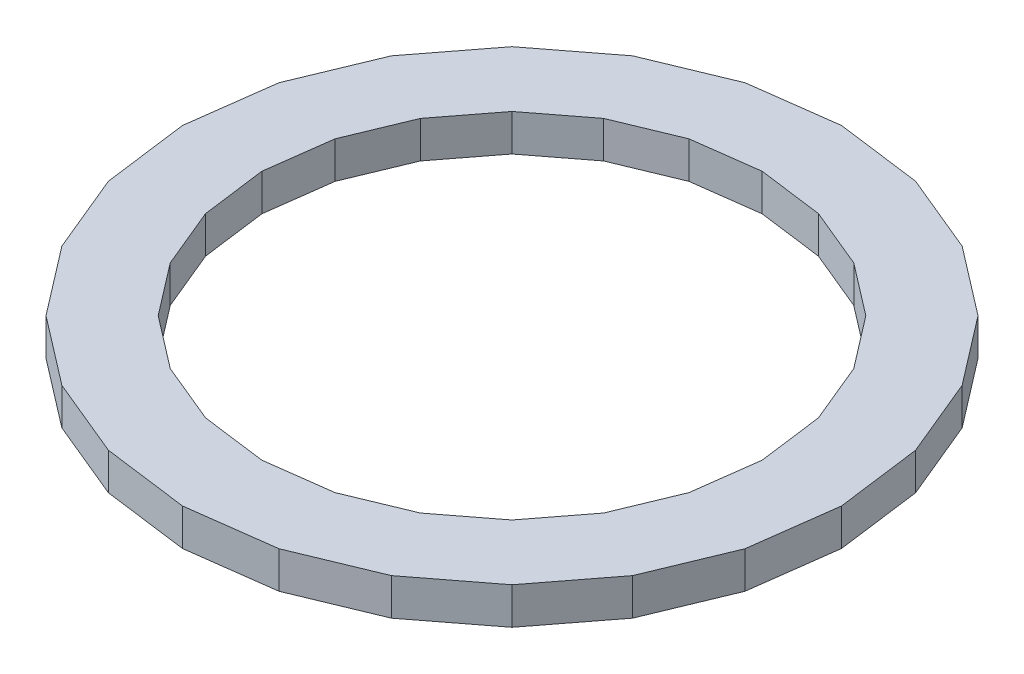
SolidWorks part; units mm, degrees
ref_plane "Front Plane" through (0, 0, 0) normal (0, 0, 1) x (1, 0, 0)
ref_plane "Top Plane" through (0, 0, 0) normal (0, 1, 0) x (1, 0, 0)
ref_plane "Right Plane" through (0, 0, 0) normal (1, 0, 0) x (0, 0, -1)
sketch "Sketch2" plane through (0, 0, 0) normal (0, 1, 0) x (1, 0, 0)
  line L0 (0, 0) -> (-129.2817, 0) construction
  line L1 (-170.2723, 0) -> (-164.4704, -44.0697)
  line L2 (-164.4704, -44.0697) -> (-147.4602, -85.1362)
  line L3 (-147.4602, -85.1362) -> (-120.4007, -120.4007)
  line L4 (-120.4007, -120.4007) -> (-85.1362, -147.4602)
  line L5 (-85.1362, -147.4602) -> (-44.0697, -164.4704)
  line L6 (-44.0697, -164.4704) -> (0, -170.2723)
  line L7 (0, -170.2723) -> (44.0697, -164.4704)
  line L8 (44.0697, -164.4704) -> (85.1362, -147.4602)
  line L9 (85.1362, -147.4602) -> (120.4007, -120.4007)
  line L10 (120.4007, -120.4007) -> (147.4602, -85.1362)
  line L11 (147.4602, -85.1362) -> (164.4704, -44.0697)
  line L12 (164.4704, -44.0697) -> (170.2723, 0)
  line L13 (170.2723, 0) -> (164.4704, 44.0697)
  line L14 (164.4704, 44.0697) -> (147.4602, 85.1362)
  line L15 (147.4602, 85.1362) -> (120.4007, 120.4007)
  line L16 (120.4007, 120.4007) -> (85.1362, 147.4602)
  line L17 (85.1362, 147.4602) -> (44.0697, 164.4704)
  line L18 (44.0697, 164.4704) -> (0, 170.2723)
  line L19 (0, 170.2723) -> (-44.0697, 164.4704)
  line L20 (-44.0697, 164.4704) -> (-85.1362, 147.4602)
  line L21 (-85.1362, 147.4602) -> (-120.4007, 120.4007)
  line L22 (-120.4007, 120.4007) -> (-147.4602, 85.1362)
  line L23 (-147.4602, 85.1362) -> (-164.4704, 44.0697)
  line L24 (-164.4704, 44.0697) -> (-170.2723, 0)
  line L25 (-129.2817, 0) -> (-124.8765, -33.4606)
  line L26 (-124.8765, -33.4606) -> (-111.9612, -64.6408)
  line L27 (-111.9612, -64.6408) -> (-91.4159, -91.4159)
  line L28 (-91.4159, -91.4159) -> (-64.6408, -111.9612)
  line L29 (-64.6408, -111.9612) -> (-33.4606, -124.8765)
  line L30 (-33.4606, -124.8765) -> (0, -129.2817)
  line L31 (0, -129.2817) -> (33.4606, -124.8765)
  line L32 (33.4606, -124.8765) -> (64.6408, -111.9612)
  line L33 (64.6408, -111.9612) -> (91.4159, -91.4159)
  line L34 (91.4159, -91.4159) -> (111.9612, -64.6408)
  line L35 (111.9612, -64.6408) -> (124.8765, -33.4606)
  line L36 (124.8765, -33.4606) -> (129.2817, 0)
  line L37 (129.2817, 0) -> (124.8765, 33.4606)
  line L38 (124.8765, 33.4606) -> (111.9612, 64.6408)
  line L39 (111.9612, 64.6408) -> (91.4159, 91.4159)
  line L40 (91.4159, 91.4159) -> (64.6408, 111.9612)
  line L41 (64.6408, 111.9612) -> (33.4606, 124.8765)
  line L42 (33.4606, 124.8765) -> (0, 129.2817)
  line L43 (0, 129.2817) -> (-33.4606, 124.8765)
  line L44 (-33.4606, 124.8765) -> (-64.6408, 111.9612)
  line L45 (-64.6408, 111.9612) -> (-91.4159, 91.4159)
  line L46 (-91.4159, 91.4159) -> (-111.9612, 64.6408)
  line L47 (-111.9612, 64.6408) -> (-124.8765, 33.4606)
  line L48 (-124.8765, 33.4606) -> (-129.2817, 0)
  line L49 (-170.2723, 0) -> (-129.2817, 0) construction
  circle A0 centre (0, 0) radius 168.8156 construction
  circle A1 centre (0, 0) radius 128.1756 construction
  dimension "D1" = 44.45
  dimension "D2" = 40.64
extrude "Boss-Extrude2" add sketch "Sketch2" along normal blind 19.05
